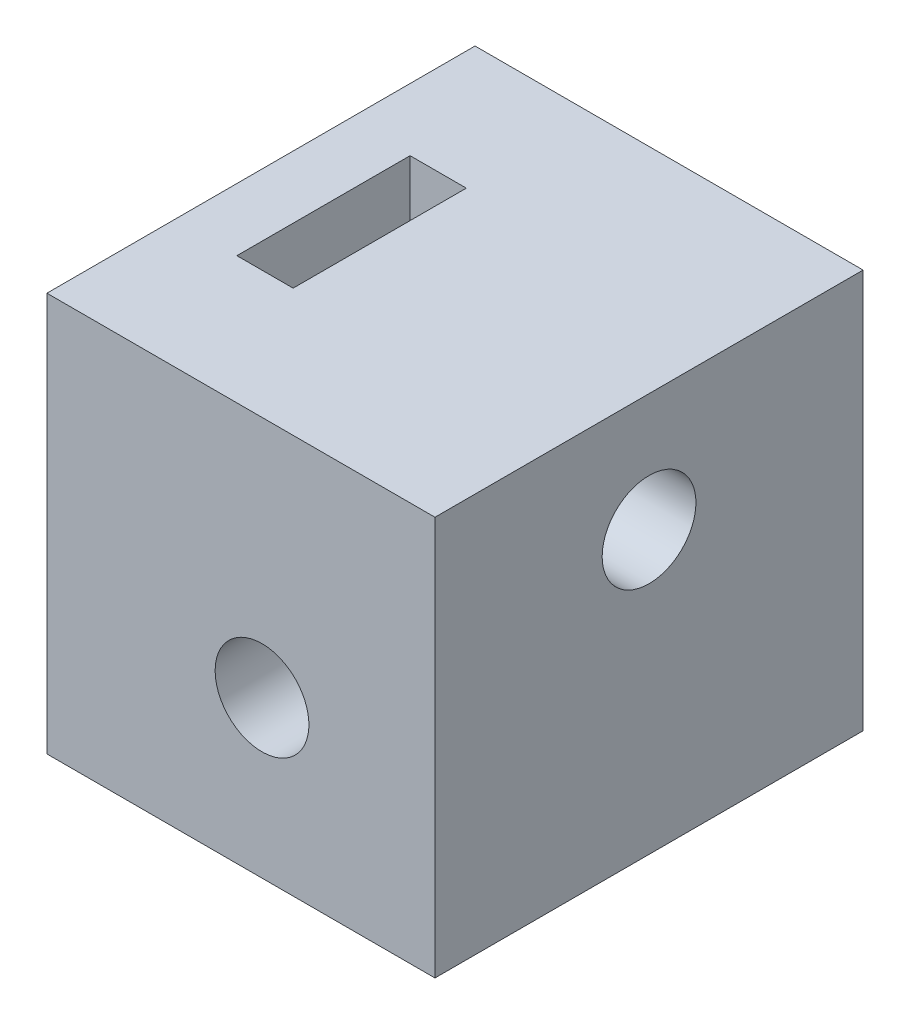
SolidWorks part; units mm, degrees
ref_plane "Front Plane" through (0, 0, 0) normal (0, 0, 1) x (1, 0, 0)
ref_plane "Top Plane" through (0, 0, 0) normal (0, 1, 0) x (1, 0, 0)
ref_plane "Right Plane" through (0, 0, 0) normal (1, 0, 0) x (0, 0, -1)
sketch "Sketch1" plane through (0, 0, 0) normal (0, 0, 1) x (1, 0, 0)
  line L0 (-5.4176, 12.7691) -> (-5.4176, 0)
  line L1 (-5.4176, 0) -> (7, 0)
  line L2 (7, 0) -> (7, 12.7691)
  line B0 (7, 0) -> (-7, 0)
  line B1 (7, 0) -> (7, 12.7691)
  line B2 (7, 12.7691) -> (-7, 12.7691)
  line B3 (-7, 0) -> (-7, 12.7691)
  line B4 (1.4655, 10) -> (1.4655, 5) construction
  line B5 (1.4655, 3.5) -> (1.4655, 0) construction
  circle B6 centre (1.4655, 5) radius 1.5
  circle B7 centre (1.4655, 10) radius 1.5
  dimension "D2" = 12.4176
sketch_block_instance "Block-bracketBlockBottomEdgesSketch-1"
sketch_block "Block-bracketBlockBottomEdgesSketch" parameters "D1"=5, "D2"=14, "D3"=3.5
extrude "Boss-Extrude1" add sketch "Sketch1" along normal blind 13.7 contours L2 B2 L0 L1 B7 B6 | B7
sketch "Sketch2" plane through (-5.4176, 0, 0) normal (-1, 0, 0) x (0, 0, 1)
  line L0 (13.7, 12.7691) -> (0, 12.7691) construction
  line L1 (0, 6.5) -> (0, 3.5) construction
  line L3 (6.85, 9) -> (6.85, 12.7691) construction
  line L6 (0, 6.5) -> (0, 3.5)
  circle A0 centre (6.85, 9) radius 1.5
  dimension "D1" = 3
  dimension "D2" = 2.5
extrude "Cut-Extrude1" cut sketch "Sketch2" against normal through all
ref_plane "Plane3" through (-3.4176, 0, 0) normal (-1, 0, 0) x (0, 0, 1)
sketch "Sketch3" plane through (-3.4176, 0, 0) normal (1, 0, 0) x (0, 0, -1)
  line L1 (-5.4644, 6.6) -> (-4.0787, 9)
  line L2 (-4.0787, 9) -> (-5.4644, 11.4)
  line L3 (-5.4644, 11.4) -> (-8.2356, 11.4)
  line L4 (-8.2356, 11.4) -> (-9.6213, 9)
  line L5 (-9.6213, 9) -> (-8.2356, 6.6)
  line L6 (-8.2356, 6.6) -> (-5.4644, 6.6)
  circle A0 centre (-6.85, 9) radius 2.4 construction
  circle A1 centre (-6.85, 9) radius 1.5 construction
  dimension "D1" = 4.8
extrude "Cut-Extrude2" cut sketch "Sketch3" along normal blind 1.8
ref_plane "Plane2" through (0, 0, 6.85) normal (0, 0, -1) x (-1, 0, 0)
sketch "Sketch5" plane through (0, 12.7691, 0) normal (0, 1, 0) x (1, 0, 0)
  line L1 (-3.4176, -4.0787) -> (-3.4176, -9.6213)
  line L2 (-3.4176, -9.6213) -> (-1.6176, -9.6213)
  line L3 (-1.6176, -9.6213) -> (-1.6176, -4.0787)
  line L4 (-1.6176, -4.0787) -> (-3.4176, -4.0787)
  point P2 (0, 0)
  point P4 (-3.4176, -4.0787)
  point P8 (-3.4176, -9.6213)
  dimension "D1" = 1.8
extrude "Cut-Extrude4" cut sketch "Sketch5" against normal up to vertex (3.7691 mm away) up to point (-3.4176, 9, 4.0787)
sketch "Sketch6" plane through (0, 6.6, 0) normal (0, 1, 0) x (1, 0, 0)
  line L1 (-3.4176, -5.4644) -> (-1.6176, -5.4644)
  line L2 (-3.4176, -5.4644) -> (-3.4176, -8.2356)
  line L3 (-3.4176, -8.2356) -> (-1.6176, -8.2356)
  line L4 (-1.6176, -5.4644) -> (-1.6176, -8.2356)
extrude "Cut-Extrude5" cut sketch "Sketch6" against normal through all
